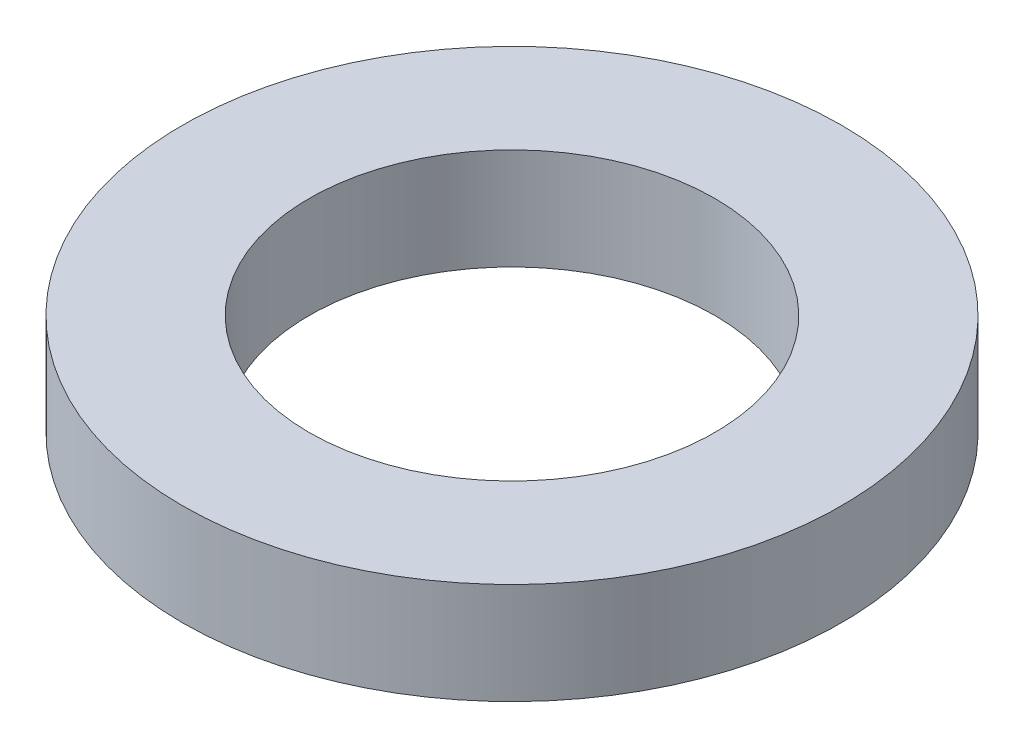
SolidWorks part; units mm, degrees
ref_plane "Front Plane" through (0, 0, 0) normal (0, 0, 1) x (1, 0, 0)
ref_plane "Top Plane" through (0, 0, 0) normal (0, 1, 0) x (1, 0, 0)
ref_plane "Right Plane" through (0, 0, 0) normal (1, 0, 0) x (0, 0, -1)
sketch "Sketch1" plane through (0, 0, 0) normal (0, 1, 0) x (1, 0, 0)
  circle A0 centre (0, 0) radius 4
  circle A1 centre (0, 0) radius 6.5
  dimension "D1" = 8
  dimension "D2" = 13
extrude "Boss-Extrude1" add sketch "Sketch1" along normal blind 2
